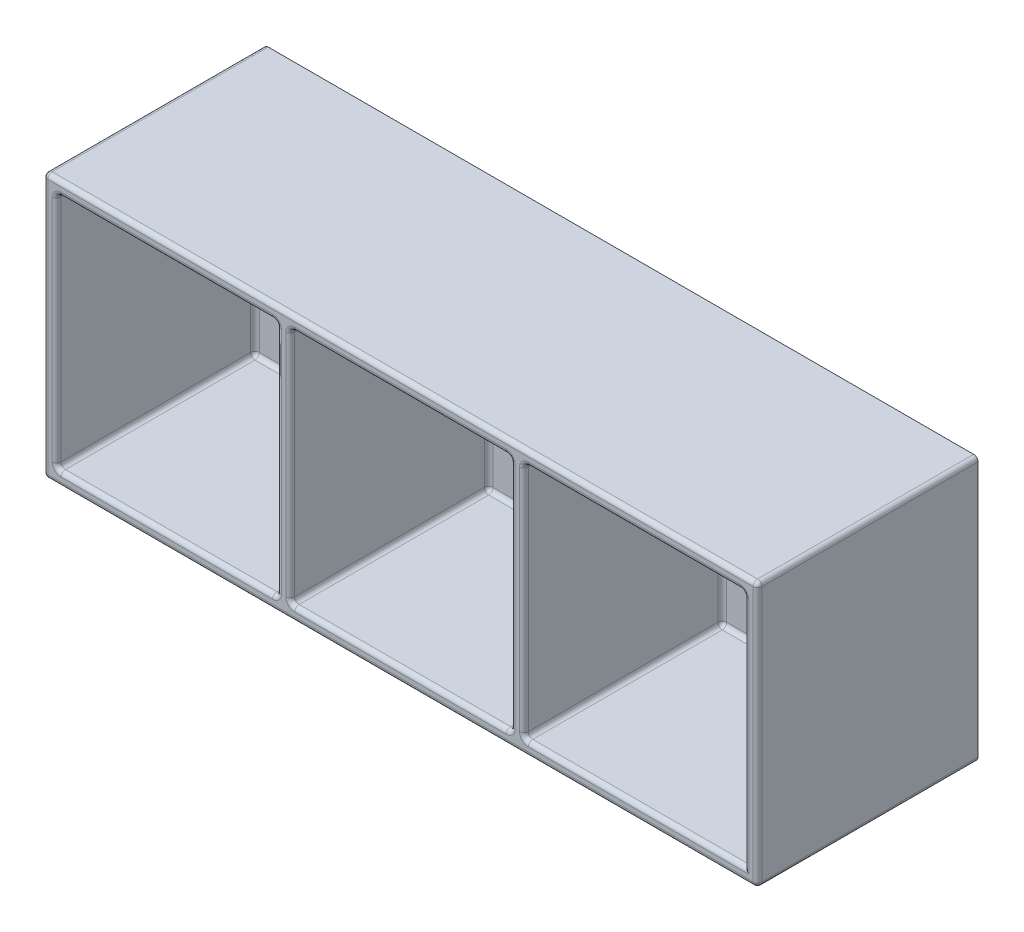
SolidWorks part; units mm, degrees
ref_plane "Front Plane" through (0, 0, 0) normal (0, 0, 1) x (1, 0, 0)
ref_plane "Top Plane" through (0, 0, 0) normal (0, 1, 0) x (1, 0, 0)
ref_plane "Right Plane" through (0, 0, 0) normal (1, 0, 0) x (0, 0, -1)
sketch "Sketch1" plane through (0, 0, 0) normal (0, 0, 1) x (1, 0, 0)
  line L1 (81, -30) -> (-81, -30)
  line L2 (81, -30) -> (81, 30)
  line L3 (81, 30) -> (-81, 30)
  line L4 (-81, -30) -> (-81, 30)
  line L5 (81, -30) -> (-81, 30) construction
  line L6 (81, 30) -> (-81, -30) construction
  point P0 (0, 0)
  dimension "D1" = 60
  dimension "D2" = 162
extrude "Boss-Extrude1" add sketch "Sketch1" along normal blind 50
sketch "Sketch2" plane through (0, 0, 50) normal (0, 0, 1) x (1, 0, 0)
  line L0 (-81, 30) -> (-81, -30) construction
  line L1 (-28, -27) -> (-78, -27)
  line L2 (-28, -27) -> (-28, 27)
  line L3 (-28, 27) -> (-78, 27)
  line L4 (-78, -27) -> (-78, 27)
  line L5 (-28, -27) -> (-78, 27) construction
  line L6 (-28, 27) -> (-78, -27) construction
  line L7 (25, -27) -> (-25, -27)
  line L8 (25, -27) -> (25, 27)
  line L9 (25, 27) -> (-25, 27)
  line L10 (-25, -27) -> (-25, 27)
  line L11 (25, -27) -> (-25, 27) construction
  line L12 (25, 27) -> (-25, -27) construction
  line L13 (78, -27) -> (28, -27)
  line L14 (78, -27) -> (78, 27)
  line L15 (78, 27) -> (28, 27)
  line L16 (28, -27) -> (28, 27)
  line L17 (78, -27) -> (28, 27) construction
  line L18 (78, 27) -> (28, -27) construction
  line L19 (81, -30) -> (81, 30) construction
  line L20 (81, 30) -> (-81, 30) construction
  line L21 (-81, -30) -> (81, -30) construction
  point P0 (-53, 0)
  point P5 (0, 0)
  point P11 (53, 0)
  dimension "D1" = 3
  dimension "D2" = 3
  dimension "D3" = 50
  dimension "D4" = 3
  dimension "D5" = 3
  dimension "D6" = 3
  dimension "D7" = 3
  dimension "D8" = 3
extrude "Cut-Extrude1" cut sketch "Sketch2" against normal blind 45
fillet "Fillet1" radius 1 43 edges at (53, -27, 50) (81, 30, 25) (81, -30, 25) (-81, 30, 25) (-81, -30, 25) (-28, 27, 27.5) (-25, -27, 27.5) (25, 27, 27.5) (78, 0, 5) (53, 27, 5) (78, 27, 27.5) (53, -27, 5) (28, -27, 27.5) (28, 0, 5) (25, -27, 27.5) (25, 0, 5) (0, -27, 5) (-28, -27, 27.5) (-53, -27, 5) (-28, 0, 5) (28, 27, 27.5) (0, 27, 5) (-25, 0, 5) (-25, 27, 27.5) (-53, 27, 5) (-78, 27, 27.5) (-78, 0, 5) (-78, -27, 27.5) (-53, -27, 50) (0, -27, 50) (78, 0, 50) (53, 27, 50) (28, 0, 50) (25, 0, 50) (-28, 0, 50) (-25, 0, 50) (0, 27, 50) (-53, 27, 50) (-78, 0, 50) (81, 0, 50) (0, -30, 50) (0, 30, 50) (-81, 0, 50)
